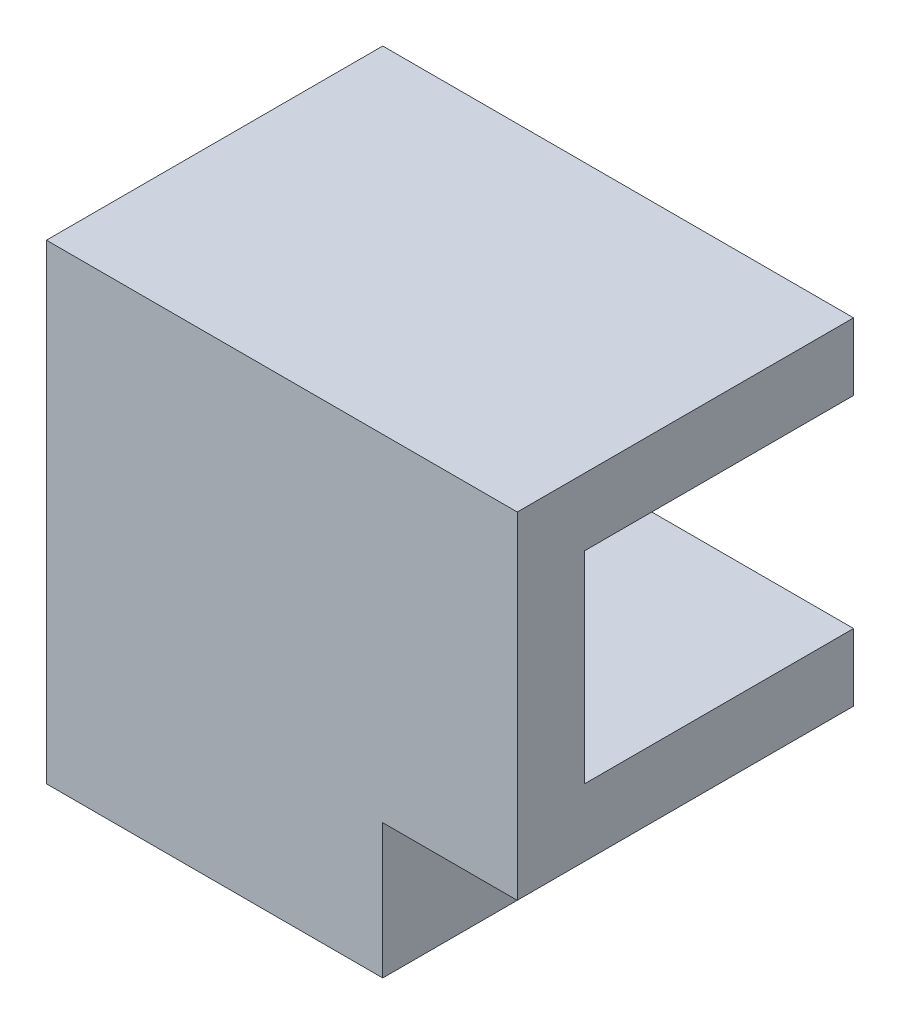
SolidWorks part; units mm, degrees
ref_plane "Plan de face" through (0, 0, 0) normal (0, 0, 1) x (1, 0, 0)
ref_plane "Plan de dessus" through (0, 0, 0) normal (0, 1, 0) x (1, 0, 0)
ref_plane "Plan de droite" through (0, 0, 0) normal (1, 0, 0) x (0, 0, -1)
sketch "Esquisse1" plane through (0, 0, 0) normal (0, 0, 1) x (1, 0, 0)
  line L0 (-1.3179, -4.6336) -> (-1.3179, -2.6336)
  line L1 (-6.3179, 2.3664) -> (0.6821, 2.3664)
  line L2 (-6.3179, 2.3664) -> (-6.3179, -4.6336)
  line L3 (-6.3179, -4.6336) -> (-1.3179, -4.6336)
  line L4 (0.6821, 2.3664) -> (0.6821, -2.6336)
  line L5 (-1.3179, -2.6336) -> (0.6821, -2.6336)
  dimension "D1" = 7
  dimension "D2" = 7
  dimension "D3" = 5
  dimension "D4" = 5
extrude "Boss.-Extru.1" add sketch "Esquisse1" along normal blind 5
sketch "Esquisse2" plane through (0, -4.6336, 0) normal (0, -1, 0) x (1, 0, 0)
  line L0 (-6.3179, 0) -> (-1.3179, 0) construction
  line L1 (-5.3179, 0) -> (-2.3179, 0)
  line L2 (-5.3179, 0) -> (-5.3179, 4)
  line L3 (-5.3179, 4) -> (-2.3179, 4)
  line L4 (-2.3179, 0) -> (-2.3179, 4)
  line L5 (-6.3179, 5) -> (-6.3179, 0) construction
  line L6 (-1.3179, 5) -> (-1.3179, 0) construction
  line L7 (-6.3179, 5) -> (-1.3179, 5) construction
  dimension "D1" = 1
  dimension "D2" = 1
  dimension "D3" = 1
extrude "Enlèv. mat.-Extru.1" cut sketch "Esquisse2" against normal blind 6
sketch "Esquisse3" plane through (0.6821, 0, 0) normal (1, 0, 0) x (0, 0, -1)
  line L0 (0, -2.6336) -> (0, 2.3664) construction
  line L1 (0, 1.3664) -> (-4, 1.3664)
  line L2 (0, 1.3664) -> (0, -1.6336)
  line L3 (0, -1.6336) -> (-4, -1.6336)
  line L4 (-4, 1.3664) -> (-4, -1.6336)
  line L5 (-5, -2.6336) -> (0, -2.6336) construction
  line L6 (-5, 2.3664) -> (0, 2.3664) construction
  line L7 (-5, -2.6336) -> (-5, 2.3664) construction
  dimension "D1" = 1
  dimension "D2" = 1
  dimension "D3" = 1
extrude "Enlèv. mat.-Extru.2" cut sketch "Esquisse3" against normal blind 6
